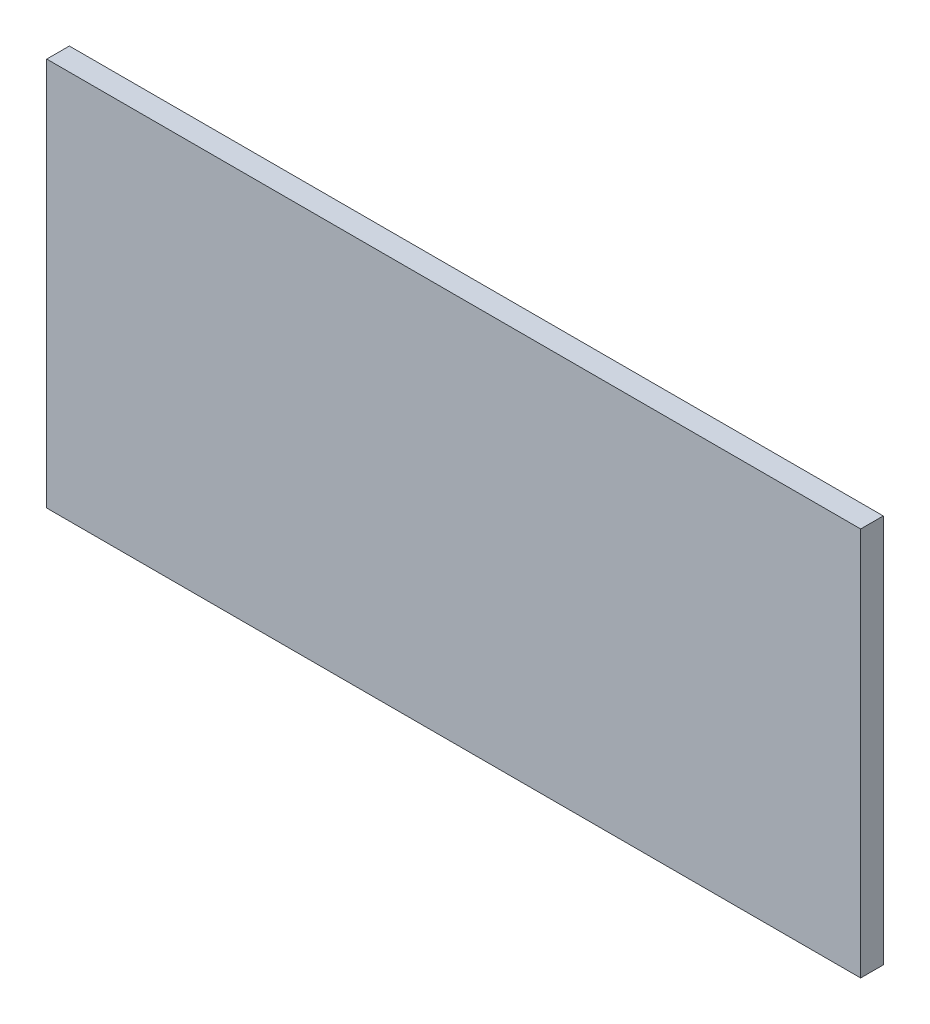
SolidWorks part; units mm, degrees
ref_plane "前基準面" through (0, 0, 0) normal (0, 0, 1) x (1, 0, 0)
ref_plane "上基準面" through (0, 0, 0) normal (0, 1, 0) x (1, 0, 0)
ref_plane "右基準面" through (0, 0, 0) normal (1, 0, 0) x (0, 0, -1)
sketch "草圖1" plane through (0, 0, 0) normal (0, 0, 1) x (1, 0, 0)
  line L1 (45, -21.5) -> (-45, -21.5)
  line L2 (45, -21.5) -> (45, 21.5)
  line L3 (45, 21.5) -> (-45, 21.5)
  line L4 (-45, -21.5) -> (-45, 21.5)
  line L5 (0, 21.5) -> (0, -21.5) construction
  line L6 (45, 0) -> (-45, 0) construction
  point P0 (0, 0)
  dimension "D1" = 90
  dimension "D2" = 43
extrude "填料-伸長1" add sketch "草圖1" along normal blind 2.5
